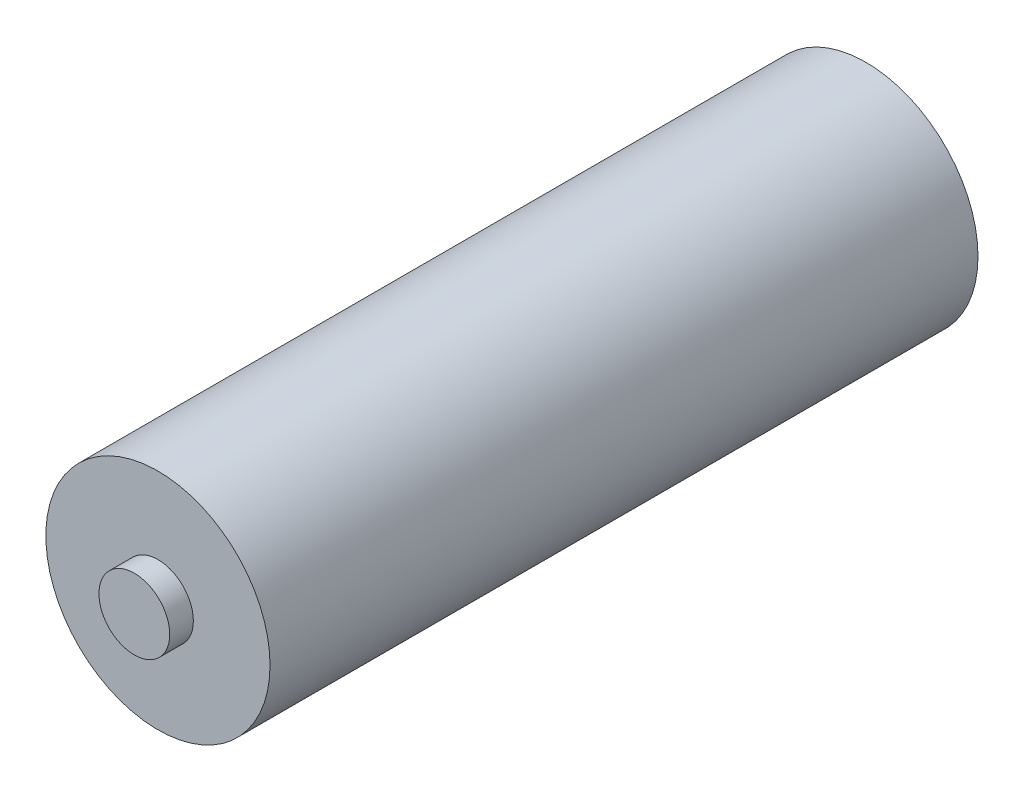
SolidWorks part; units mm, degrees
ref_plane "Front Plane" through (0, 0, 0) normal (0, 0, 1) x (1, 0, 0)
ref_plane "Top Plane" through (0, 0, 0) normal (0, 1, 0) x (1, 0, 0)
ref_plane "Right Plane" through (0, 0, 0) normal (1, 0, 0) x (0, 0, -1)
sketch "Sketch1" plane through (0, 0, 0) normal (0, 0, 1) x (1, 0, 0)
  circle A0 centre (0, 0) radius 47.5
  dimension "D1" = 95
extrude "Boss-Extrude1" add sketch "Sketch1" along normal mid plane 300
sketch "Sketch2" plane through (0, 0, 150) normal (0, 0, 1) x (1, 0, 0)
  circle A0 centre (0, 0) radius 15
  dimension "D1" = 30
extrude "Boss-Extrude2" add sketch "Sketch2" along normal blind 10 and the other way blind 310
